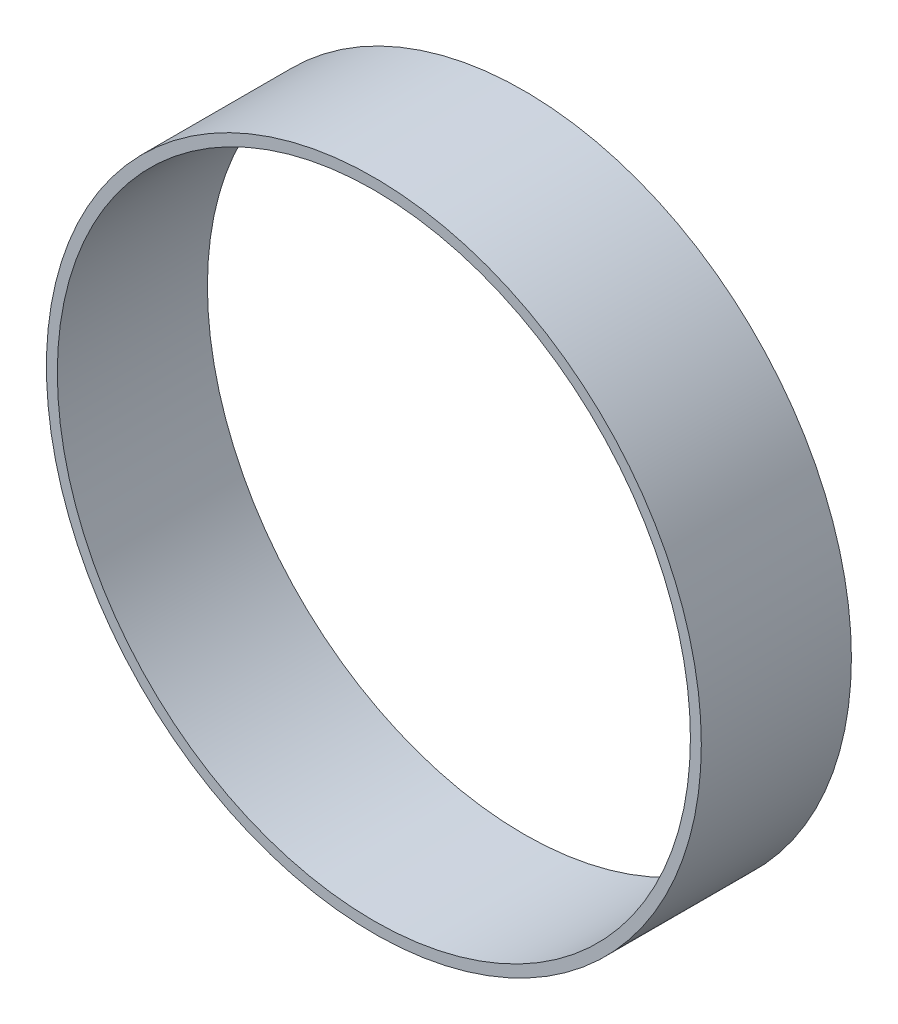
SolidWorks part; units mm, degrees
ref_plane "Front Plane" through (0, 0, 0) normal (0, 0, 1) x (1, 0, 0)
ref_plane "Top Plane" through (0, 0, 0) normal (0, 1, 0) x (1, 0, 0)
ref_plane "Right Plane" through (0, 0, 0) normal (1, 0, 0) x (0, 0, -1)
sketch "Sketch1" plane through (0, 0, 0) normal (0, 0, 1) x (1, 0, 0)
  circle A0 centre (0, 0) radius 76.2
  circle A1 centre (0, 0) radius 73.66
  dimension "D2" = 152.4
  dimension "D1" = 2.54
extrude "Boss-Extrude1" add sketch "Sketch1" along normal blind 34.925
